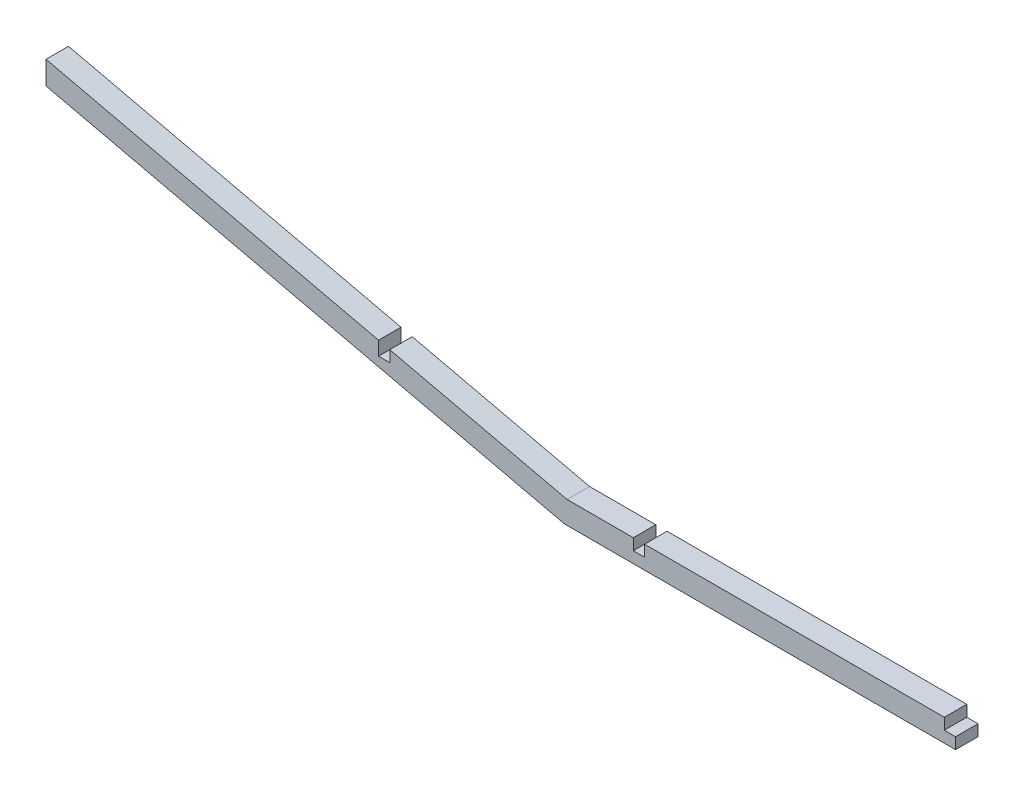
SolidWorks part; units mm, degrees
ref_plane "Front Plane" through (0, 0, 0) normal (0, 0, 1) x (1, 0, 0)
ref_plane "Top Plane" through (0, 0, 0) normal (0, 1, 0) x (1, 0, 0)
ref_plane "Right Plane" through (0, 0, 0) normal (1, 0, 0) x (0, 0, -1)
sketch "Sketch1" plane through (0, 0, 0) normal (0, 0, 1) x (1, 0, 0)
  line L0 (0, 0) -> (0, 3)
  line L1 (0, 3) -> (-3, 3)
  line L2 (-3, 3) -> (-3, 6)
  line L3 (-3, 6) -> (-83, 6)
  line L4 (-83, 6) -> (-83, 3)
  line L5 (-83, 3) -> (-86, 3)
  line L6 (-86, 3) -> (-86, 6)
  line L7 (-86, 6) -> (-103.6765, 6)
  line L8 (-103.6765, 6) -> (-151, 16.96)
  line L9 (-151, 16.96) -> (-151, 13.96)
  line L10 (-151, 13.96) -> (-154, 13.96)
  line L11 (-154, 13.96) -> (-154, 17.6548)
  line L12 (-154, 17.6548) -> (-242.75, 38.2091)
  line L13 (-242.75, 38.2091) -> (-242.75, 32.0503)
  line L14 (-242.75, 32.0503) -> (-104.3623, 0)
  line L15 (-104.3623, 0) -> (0, 0)
  line L16 (-151, 16.96) -> (-154, 17.6548) construction
  point P3 (0, 0)
  point P18 (-92.1811, 4.3823)
  point P19 (-128.2698, 22.5148)
  dimension "D1" = 3
  dimension "D2" = 3
  dimension "D3" = 3
  dimension "D4" = 3
  dimension "D5" = 3
  dimension "D6" = 80
  dimension "D7" = 3
  dimension "D8" = 3
  dimension "D9" = 6
  dimension "D10" = 65
  dimension "D11" = 10.96
  dimension "D12" = 88.75
extrude "Boss-Extrude1" add sketch "Sketch1" along normal blind 6 contours L14 L15 L0 L1 L2 L3 L4 L5 L6 L7 L8 L9 L10 L11 L12 L13
